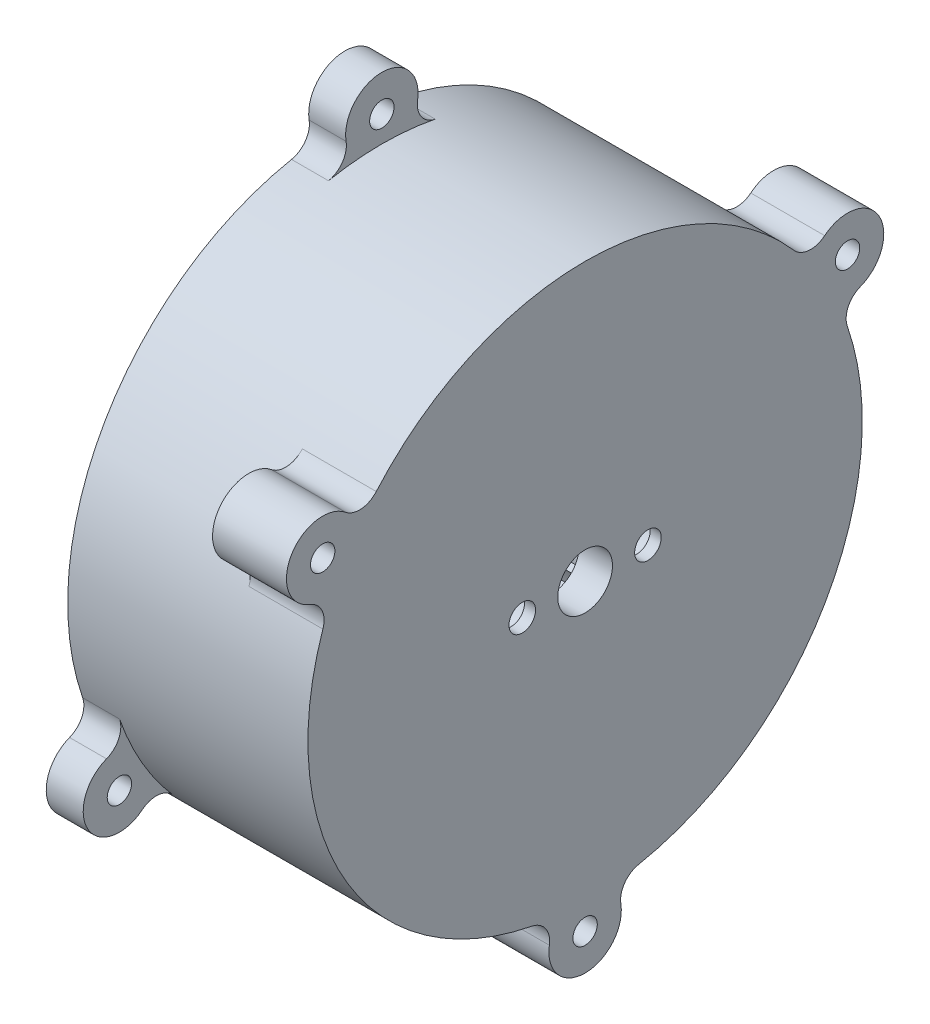
SolidWorks part; units mm, degrees
ref_plane "Plane1" through (0, 0, 0) normal (0, 0, 1) x (1, 0, 0)
ref_plane "Plane2" through (0, 0, 0) normal (0, 1, 0) x (1, 0, 0)
ref_plane "Plane3" through (0, 0, 0) normal (1, 0, 0) x (0, 0, -1)
sketch "HoldingSke" plane through (0, 0, 0) normal (0, 1, 0) x (1, 0, 0)
  line L0 (0, 0) -> (0.4589, -0.6553)
  line L1 (-15, 0) -> (100, 0) construction
  line L2 (0, 0) -> (-2.1039, 2.3779)
  line L3 (0, 0) -> (-11.863, 4.5341)
  line L4 (0, 0) -> (4.9534, 7.0742)
  line L5 (0, 0) -> (-23.7986, -8.8762)
  line L6 (0, 0) -> (-10.5278, -7.1032)
  line L7 (-2.1039, 2.3779) -> (3.3635, 27.1825)
  line L8 (-76.2, 3.6279) -> (-54.61, 3.6279)
  line L9 (-67.7845, 28.3722) -> (-49.3413, 33.142)
  line L10 (-76.2, 71.12) -> (104.1128, 71.12)
  line L11 (0, 0) -> (-28, 0)
  line L12 (-76.2, 101.6) -> (-76.155, 101.6)
  line L13 (24.9733, 27.94) -> (52.9518, 28.4284)
  line L14 (24.9733, 27.94) -> (24.9743, 27.94)
  line L15 (24.9733, 27.94) -> (100.4006, 29.5858)
  circle A0 centre (0, 0) radius 37.5
  circle A1 centre (0, 0) radius 12.7
  circle A2 centre (0, 0) radius 12.7
  dimension "MHD" = 25.4
  dimension "Hub_dia" = 25.4
  dimension "Diameter" = 75
  dimension "Num_teeth" = 55
  dimension "Pitch" = 0.8
  dimension "Overall_len" = 25.4
  dimension "Show_teeth" = 55
  dimension "Thickness" = 12.7
  dimension "OAL" = 25.4001
  dimension "T_dim" = 21.59
  dimension "Ap" = 14.5
  dimension "H" = 19.05
  dimension "Pitch_radius" = 180.3128
  dimension "Width" = 28
  dimension "Backlash" = 0.045
  dimension "Addendum_fac" = 1
  dimension "Dedendum_fac" = 1.25
  dimension "Clearance_fac" = 0.25
  dimension "Dedendum_add" = 0.001
  dimension "Module" = 1.25
sketch "BasProSke" plane through (0, 0, 0) normal (0, 1, 0) x (1, 0, 0)
  line L0 (-10, 0) -> (60, 0) construction
  line L1 (0, 33.125) -> (0, 37.5)
  line L2 (0, 33.125) -> (28, 33.125)
  line L3 (28, 33.125) -> (28, 37.5)
  line L4 (28, 37.5) -> (0, 37.5)
  dimension "Diameter" = 75
  dimension "Thickness" = 28
  dimension "Inside_diameter" = 66.25
revolve "Base-Revolve" add sketch "BasProSke" angle 360 about L0
sketch "TooCutSke" plane through (0, 0, 0) normal (1, 0, 0) x (0, 0, -1)
  line L3 (1.0941, 34.3576) -> (1.0941, 53.6633) construction
  line L4 (0, 0) -> (0, 59.563) construction
  line L5 (0, 0) -> (-3.9007, 68.2161) construction
  line L6 (-15.2783, 29.1274) -> (36.0712, 32.0636) construction
  circle A0 centre (0, 0) radius 34.375 construction
  circle A1 centre (0, 0) radius 35.9385 construction
  circle A2 centre (0, 0) radius 29.9521 construction
  circle A3 centre (0, 0) radius 33.0996 construction
  arc A4 (1.4514, 33.0678) -> (0.5036, 35.935) centre (-15.2783, 29.1274) ccw
  arc A5 (1.4514, 33.0678) -> (-1.4514, 33.0678) centre (0, 0) ccw
  arc A6 (0.5036, 35.935) -> (-0.5036, 35.935) centre (0, 0) ccw
  arc A7 (-0.5036, 35.935) -> (-1.4514, 33.0678) centre (15.2783, 29.1274) ccw
  dimension "Pitch_dia" = 68.75
  dimension "Base_dia" = 59.9041
  dimension "Root_dia" = 71.877
  dimension "Overcut_dia" = 66.1992
  dimension "Flank_rad" = 17.1875
  dimension "Half_ang" = 3.273
  dimension "Half_CT" = 1.0941
extrude "ToothCut" cut sketch "TooCutSke" along normal through all
fillet "Breaks" [suppressed] radius 0.125
fillet "RootFillets" [suppressed] radius 0.3135
pattern_circular "TeethCuts" count 55 every 6.545 about axis through (-10, 0, 0) along (1, 0, 0) of "RootFillets", "Breaks", "ToothCut"
sketch "Sketch1" plane through (28, 0, 0) normal (1, 0, 0) x (0, 0, -1)
  circle A0 centre (0, 0) radius 37.5
extrude "Boss-Extrude1" add sketch "Sketch1" along normal blind 4.5
sketch "Sketch2" plane through (32.5, 0, 0) normal (1, 0, 0) x (0, 0, -1)
  circle A0 centre (0, 0) radius 3.7
  circle A1 centre (-8.5, 0) radius 1.8
  circle A2 centre (8.5, 0) radius 1.8
  dimension "D1" = 7.4
  dimension "D2" = 3.6
  dimension "D3" = 8.5
  dimension "D4" = 8.5
extrude "Cut-Extrude1" cut sketch "Sketch2" against normal blind 4.5
sketch "Sketch3" plane through (28, 0, 0) normal (-1, 0, 0) x (0, 0, 1)
  circle A0 centre (-8.5, 0) radius 3.25
  circle A1 centre (8.5, 0) radius 3.25
  dimension "D1" = 6.5
extrude "Cut-Extrude2" cut sketch "Sketch3" against normal blind 3
sketch "Sketch4" plane through (0, 0, 0) normal (-1, 0, 0) x (0, 0, 1)
  line L0 (0, 0) -> (0, 45.9) construction
  circle A0 centre (0, 41) radius 1.65
  circle A1 centre (0, 0) radius 3.7 construction
  circle A2 centre (35.507, -20.5) radius 1.65
  circle A3 centre (-35.507, -20.5) radius 1.65
  arc A4 (-3.2765, 37.3566) -> (3.2765, 37.3566) centre (0, 41) cw
  circle A5 centre (0, 0) radius 37.5 construction
  arc A6 (-3.2765, 37.3566) -> (3.2765, 37.3566) centre (0, 0) cw
  arc A7 (33.99, -15.8408) -> (30.7135, -21.5158) centre (35.507, -20.5) cw
  arc A8 (33.99, -15.8408) -> (30.7135, -21.5158) centre (0, 0) cw
  arc A9 (-30.7135, -21.5158) -> (-33.99, -15.8408) centre (-35.507, -20.5) cw
  arc A10 (-30.7135, -21.5158) -> (-33.99, -15.8408) centre (0, 0) cw
  point P11 (0, 0)
  point P28 (0, 0)
  dimension "D1" = 3.3
  dimension "D2" = 41
  dimension "D5" = 3
  dimension "D4" = 45.9
  dimension "D3" = 3
extrude "Boss-Extrude2" add sketch "Sketch4" against normal blind 5
fillet "Fillet1" radius 3 6 edges at (2.5, -15.8408, -33.99) (2.5, -21.5158, -30.7135) (2.5, -15.8408, 33.99) (2.5, -21.5158, 30.7135) (2.5, 37.3566, -3.2765) (2.5, 37.3566, 3.2765)
sketch "Sketch5" plane through (32.5, 0, 0) normal (1, 0, 0) x (0, 0, -1)
  line L0 (0, 0) -> (35.507, 20.5) construction
  line L1 (0, 0) -> (0, 41) construction
  circle A1 centre (35.507, 20.5) radius 1.65
  circle A2 centre (0, -41) radius 1.65
  circle A3 centre (-35.507, 20.5) radius 1.65
  arc A4 (33.99, 15.8408) -> (30.7135, 21.5158) centre (35.507, 20.5) ccw
  circle A5 centre (0, 0) radius 37.5 construction
  arc A6 (30.7135, 21.5158) -> (33.99, 15.8408) centre (0, 0) cw
  arc A7 (-3.2765, -37.3566) -> (3.2765, -37.3566) centre (0, -41) ccw
  arc A8 (3.2765, -37.3566) -> (-3.2765, -37.3566) centre (0, 0) cw
  arc A9 (-30.7135, 21.5158) -> (-33.99, 15.8408) centre (-35.507, 20.5) ccw
  arc A10 (-33.99, 15.8408) -> (-30.7135, 21.5158) centre (0, 0) cw
  point P13 (0, 0)
  point P26 (0, 0)
  dimension "D2" = 3.3
  dimension "D4" = 3
  dimension "D1" = 60
  dimension "D3" = 3
extrude "Boss-Extrude3" add sketch "Sketch5" against normal blind 10
fillet "Fillet2" radius 3 6 edges at (27.5, 21.5158, 30.7135) (27.5, 15.8408, 33.99) (27.5, -37.3566, -3.2765) (27.5, -37.3566, 3.2765) (27.5, 21.5158, -30.7135) (27.5, 15.8408, -33.99)
equation "' \"Module@HoldingSke\" = 6.35"
equation "' \"Num_teeth@HoldingSke\" = 24"
equation "' \"Ap@HoldingSke\" =  14.5"
equation "' \"Ap@HoldingSke\" = 14.5"
equation "' \"Width@HoldingSke\" = 12"
equation "' \"Diameter@HoldingSke\" = 8 * 25.4"
equation "' \"Show_teeth@HoldingSke\" = 100"
equation "' \"Backlash@HoldingSke\" = 0.009 * 25.4"
equation "' \"Addendum_fac@HoldingSke\" = 1.0"
equation "' \"Dedendum_fac@HoldingSke\" = 1.25"
equation "' \"Dedendum_add@HoldingSke\" = 0.00005 * 25.4"
equation "' \"Clearance_fac@HoldingSke\" = 0.25"
equation "\"Pitch@HoldingSke\" = 1 / \"Module@HoldingSke\" "
equation "\"Overcut_dia@TooCutSke\" = (\"Num_teeth@HoldingSke\" - 2 * \"Addendum_fac@HoldingSke\") / \"Pitch@HoldingSke\" - 0.002 * 25.4"
equation "\"Pitch_dia@TooCutSke\" = \"Num_teeth@HoldingSke\" / \"Pitch@HoldingSke\""
equation "\"Base_dia@TooCutSke\" = \"Num_teeth@HoldingSke\" / \"Pitch@HoldingSke\" * cos((\"Ap@HoldingSke\"  * 3.14159265 / 180)) * 0.90"
equation "\"Root_dia@TooCutSke\" = \"Num_teeth@HoldingSke\"  / \"Pitch@HoldingSke\" + 2 *  \"Dedendum_fac@HoldingSke\"/ \"Pitch@HoldingSke\" + \"Dedendum_add@HoldingSke\" * 2"
equation "\"Half_ang@TooCutSke\" = 180 / \"Num_teeth@HoldingSke\""
equation "\"Half_CT@TooCutSke\" = \"Num_teeth@HoldingSke\" / \"Pitch@HoldingSke\" * sin((3.14159265 / 2 / \"Num_teeth@HoldingSke\")) / 2 + 10 * \"Backlash@HoldingSke\" / 4"
equation "\"Flank_rad@TooCutSke\" = \"Num_teeth@HoldingSke\" / \"Pitch@HoldingSke\" / 4"
equation "\"Radius@RootFillets\"= \"Clearance_fac@HoldingSke\" / \"Pitch@HoldingSke\" + \"Dedendum_add@HoldingSke\""
equation "\"Break_rad@Breaks\" = 0.02 / \"Pitch@HoldingSke\" * 5"
equation "\"Num_teeth@TeethCuts\" = int( \"Show_teeth@HoldingSke\" ) + 1"
equation "\"Num_teeth@TeethCuts\" = ((sgn( \"Num_teeth@TeethCuts\" - \"Num_teeth@HoldingSke\" )-1)*( \"Num_teeth@TeethCuts\" - \"Num_teeth@HoldingSke\" ))/-2+ \"Num_teeth@HoldingSke\""
equation "\"Num_teeth@TeethCuts\" = ((sgn( \"Num_teeth@TeethCuts\" - 2.0)+1)*( \"Num_teeth@TeethCuts\" - 2.0))/2 +2.0"
equation "\"Angle@TeethCuts\" = 360.0 / \"Num_teeth@HoldingSke\""
equation "\"Diameter@BasProSke\" = \"Num_teeth@HoldingSke\"  / \"Pitch@HoldingSke\" + 2 *  \"Dedendum_fac@HoldingSke\"/ \"Pitch@HoldingSke\" + \"Dedendum_add@HoldingSke\" * 2 + 0.002 * 25.4"
equation "\"Diameter@BasProSke\" = ((sgn( \"Diameter@BasProSke\"  - \"Diameter@HoldingSke\" )+1)*( \"Diameter@BasProSke\"  - \"Diameter@HoldingSke\" ))/2 + \"Diameter@HoldingSke\""
equation "\"Inside_diameter@BasProSke\" =  (\"Num_teeth@HoldingSke\" - 2 * \"Addendum_fac@HoldingSke\") / \"Pitch@HoldingSke\" "
equation "\"Thickness@BasProSke\"  = \"Width@HoldingSke\""
